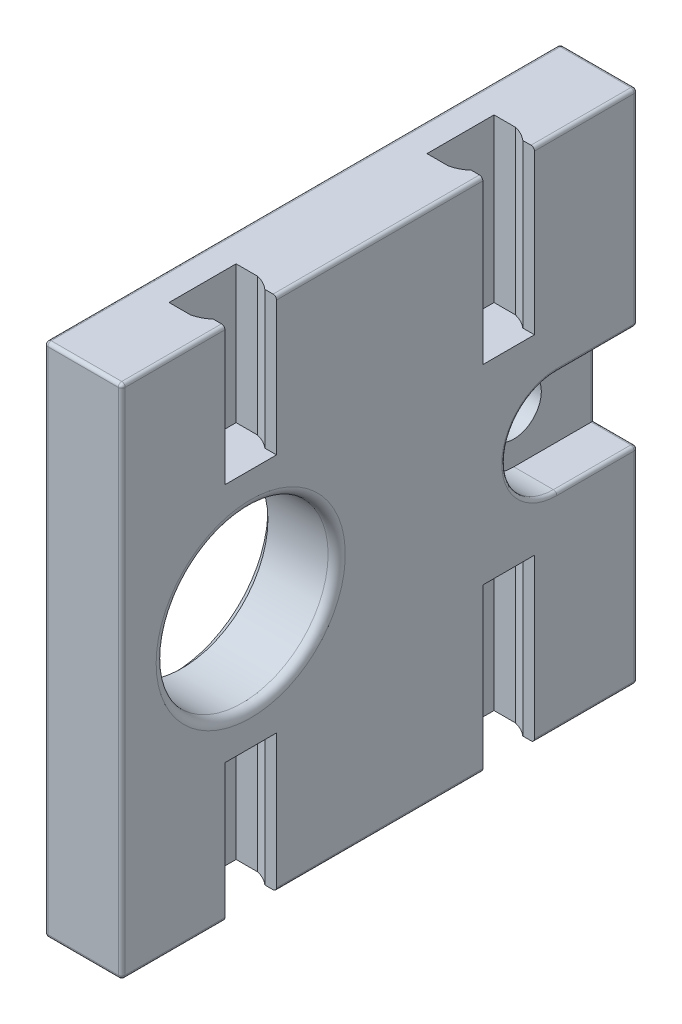
SolidWorks part; units mm, degrees
ref_plane "前视基准面" through (0, 0, 0) normal (0, 0, 1) x (1, 0, 0)
ref_plane "上视基准面" through (0, 0, 0) normal (0, 1, 0) x (1, 0, 0)
ref_plane "右视基准面" through (0, 0, 0) normal (1, 0, 0) x (0, 0, -1)
sketch "草图1" plane through (0, 0, 0) normal (1, 0, 0) x (0, 0, -1)
  line L0 (15, 15) -> (-15, 15)
  line L1 (15, 15) -> (15, -15)
  line L2 (-15, 15) -> (-15, -15)
  line L3 (15, -15) -> (-15, -15)
  line L4 (15, 15) -> (-15, -15) construction
  line L5 (-15, 15) -> (15, -15) construction
  point P1 (0, 0)
  dimension "D1" = 15
  dimension "D2" = 15
extrude "凸台-拉伸1" add sketch "草图1" along normal blind 4.5
sketch "草图2" plane through (4.5, 0, 0) normal (1, 0, 0) x (0, 0, -1)
  line L0 (0, 0) -> (-7.5, 0) construction
  line L1 (0, 0) -> (10.3, 0) construction
  circle A0 centre (-7.5, 0) radius 5
  circle A1 centre (10.3, 0) radius 1.6
  dimension "D2" = 10
  dimension "D4" = 3.2
  dimension "D1" = 7.5
  dimension "D3" = 10.3
extrude "切除-拉伸1" cut sketch "草图2" against normal through all
sketch "草图3" plane through (4.5, 0, 0) normal (1, 0, 0) x (0, 0, -1)
  line L0 (10.3, 3) -> (15, 3)
  line L1 (15, -15) -> (15, 15) construction
  line L2 (10.3, -3) -> (15, -3)
  line L3 (15, 3) -> (15, -3)
  arc A2 (10.3, 3) -> (10.3, -3) centre (10.3, 0) ccw
  dimension "D1" = 3
  dimension "D2" = 4.7
  dimension "D3" = 10.3
extrude "切除-拉伸2" cut sketch "草图3" against normal blind 2.5
sketch "草图4" plane through (0, -15, 0) normal (0, -1, 0) x (1, 0, 0)
  line L0 (0, 0) -> (0, 7.5) construction
  line L1 (0, 15) -> (0, -15) construction
  line L2 (0, 7.5) -> (2.5, 7.5) construction
  line L3 (2.5, 7.5) -> (4.5, 7.5) construction
  line L4 (4.5, 15) -> (4.5, -15) construction
  line L5 (4.5, 7.5) -> (1.7, 7.5) construction
  line L6 (1.7, 5.55) -> (1.7, 9.45)
  line L7 (1.7, 9.45) -> (2.9444, 9.45)
  line L8 (4.5, 6) -> (4.5, 9)
  line L9 (4.5, 9) -> (3.8229, 9)
  line L10 (4.5, 6) -> (3.8229, 6)
  line L11 (1.7, 5.55) -> (2.9444, 5.55)
  arc A0 (3.8229, 9) -> (2.9444, 9.45) centre (2.5, 7.5) ccw
  arc A1 (3.8229, 6) -> (2.9444, 5.55) centre (2.5, 7.5) cw
  dimension "D6" = 2
  dimension "D1" = 7.5
  dimension "D2" = 2.5
  dimension "D3" = 2.8
  dimension "D4" = 1.95
  dimension "D5" = 1.5
extrude "切除-拉伸3" cut sketch "草图4" against normal blind 8
mirror "镜向1" about plane through (0, 0, 0) normal (0, 1, 0) of "切除-拉伸3"
sketch "草图5" plane through (0, -15, 0) normal (0, -1, 0) x (1, 0, 0)
  line L0 (0, 0) -> (0, -7.5) construction
  line L1 (0, 15) -> (0, -15) construction
  line L2 (0, -7.5) -> (1.7, -7.5) construction
  line L3 (1.7, -7.5) -> (2.5, -7.5) construction
  line L4 (2.5, -7.5) -> (4.5, -7.5) construction
  line L5 (4.5, 6) -> (4.5, -15) construction
  line L6 (1.7, -9.45) -> (1.7, -5.55)
  line L7 (1.7, -5.55) -> (2.9444, -5.55)
  line L8 (4.5, -9) -> (4.5, -6)
  line L9 (4.5, -6) -> (3.8229, -6)
  line L10 (4.5, -9) -> (3.8229, -9)
  line L11 (1.7, -9.45) -> (2.9444, -9.45)
  arc A0 (3.8229, -6) -> (2.9444, -5.55) centre (2.5, -7.5) ccw
  arc A1 (3.8229, -9) -> (2.9444, -9.45) centre (2.5, -7.5) cw
  dimension "D6" = 2
  dimension "D1" = 7.5
  dimension "D2" = 1.7
  dimension "D3" = 2.5
  dimension "D4" = 1.95
  dimension "D5" = 1.5
extrude "切除-拉伸4" cut sketch "草图5" against normal blind 9.45
mirror "镜向2" about plane through (0, 0, 0) normal (0, 1, 0) of "切除-拉伸4"
sketch "草图6" plane through (0, 0, 0) normal (-1, 0, 0) x (0, 0, 1)
  line L0 (-3.5, 13) -> (3.5, 13)
  line L1 (-3.5, 13) -> (-3.5, 3.5)
  line L2 (3.5, 13) -> (3.5, 5.7446)
  line L3 (-3.5, -13) -> (3.5, -13)
  line L4 (-3.5, 13) -> (3.5, -13) construction
  line L5 (3.5, 13) -> (-3.5, -13) construction
  line L6 (0, 0) -> (-3.5, 0) construction
  line L7 (-3.5, -3.5) -> (-3.5, -13)
  line L8 (3.5, -5.7446) -> (3.5, -13)
  line L9 (-7, -3.5) -> (-7, 3.5)
  line L13 (-3.5, 3.5) -> (-7, 3.5)
  line L14 (-3.5, -3.5) -> (-7, -3.5)
  circle A0 centre (7.5, 0) radius 5 construction
  circle A1 centre (7.5, 0) radius 5 construction
  arc A2 (3.5, 5.7446) -> (3.5, -5.7446) centre (7.5, 0) ccw
  circle A4 centre (7.5, 0) radius 7 construction
  point P6 (0, 0)
  point P8 (14.5, 0)
  dimension "D2" = 7
  dimension "D3" = 26
  dimension "D4" = 3.5
  dimension "D5" = 7
  dimension "D6" = 3.5
  dimension "D1" = 2
extrude "切除-拉伸5" cut sketch "草图6" against normal blind 2.5
fillet "圆角1" radius 0.2 23 edges at (0, 0, 15) (4.5, 0, 15) (4.5, 15, -12) (4.5, 15, 0) (4.5, 15, 12) (2.25, 15, 15) (0, 15, 0) (2.25, 15, -15) (4.5, 3, -12.65) (4.5, -3, -12.65) (4.5, 0, -7.3) (3.25, 3, -15) (2, 0, -15) (3.25, -3, -15) (0, 0, -15) (4.5, 9, -15) (4.5, -9, -15) (2.25, -15, -15) (2.25, -15, 15) (0, -15, 0) (4.5, -15, -12) (4.5, -15, 0) (4.5, -15, 12)
fillet "圆角2" radius 0.2 10 edges at (0, 13, 0) (0, 8.25, -3.5) (0, 3.5, -5.25) (0, 0, -7) (0, -3.5, -5.25) (0, -8.25, -3.5) (0, -13, 0) (0, -9.3723, 3.5) (0, 9.3723, 3.5) (0, 0, 0.5)
chamfer "倒角1" distance 0.5 angle 45 1 edges at (0, 0, 2.5)
fillet "圆角3" radius 0.5 1 edges at (4.5, 0, 2.5)
